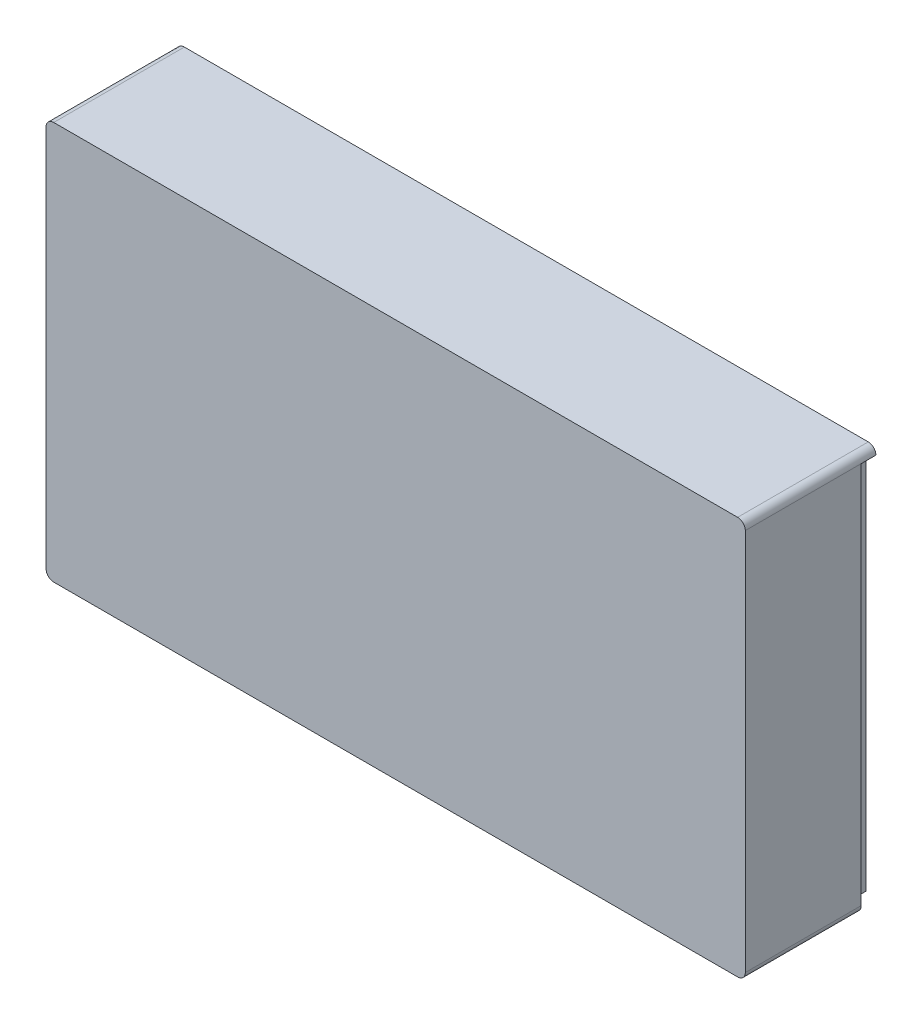
SolidWorks part; units mm, degrees
material "PETG"
ref_plane "Front Plane" through (0, 0, 0) normal (0, 0, 1) x (1, 0, 0)
ref_plane "Top Plane" through (0, 0, 0) normal (0, 1, 0) x (1, 0, 0)
ref_plane "Right Plane" through (0, 0, 0) normal (1, 0, 0) x (0, 0, -1)
sketch "Sketch2" plane through (0, 0, 0) normal (0, 0, 1) x (1, 0, 0)
  line L1 (-145, 82.55) -> (145, 82.55)
  line L2 (-145, 82.55) -> (-145, -82.55)
  line L3 (-145, -82.55) -> (145, -82.55)
  line L4 (145, 82.55) -> (145, -82.55)
  line L5 (133.825, 71.375) -> (133.825, -71.375)
  line L7 (-133.825, 71.375) -> (-133.825, -71.375)
  line L8 (-133.825, 71.375) -> (133.825, 71.375) construction
  line L9 (-133.825, 71.375) -> (-133.825, 79.375)
  line L10 (-133.825, 79.375) -> (133.825, 79.375)
  line L11 (133.825, 79.375) -> (133.825, 71.375)
  line L12 (133.825, -71.375) -> (133.825, -79.375)
  line L13 (-133.825, -71.375) -> (133.825, -71.375) construction
  line L14 (133.825, -79.375) -> (-133.825, -79.375)
  line L15 (-133.825, -79.375) -> (-133.825, -71.375)
  point P4 (0, 82.55)
  point P6 (145, 0)
  dimension "D1" = 290
  dimension "D2" = 165.1
  dimension "D4" = 3.175
  dimension "D5" = 3.175
  dimension "D3" = 11.175
extrude "Boss-Extrude1" add sketch "Sketch2" along normal blind 51
sketch "Sketch3" plane through (0, 0, 51) normal (0, 0, 1) x (1, 0, 0)
  line L0 (145, 82.55) -> (-145, 82.55) construction
  line L1 (-145, 82.55) -> (145, 82.55)
  line L2 (-145, 82.55) -> (-145, -82.55)
  line L3 (-145, -82.55) -> (145, -82.55)
  line L4 (145, 82.55) -> (145, -82.55)
extrude "Boss-Extrude2" add sketch "Sketch3" along normal blind 3.175
sketch "Sketch4" plane through (0, -82.55, 0) normal (0, -1, 0) x (1, 0, 0)
  line L0 (145, 54.175) -> (145, 0) construction
  line L1 (140.9, 2.9) -> (136.9, 2.9)
  line L2 (145, 2.9) -> (145, 6.1)
  line L3 (145, 6.1) -> (136.9, 6.1)
  line L4 (136.9, 2.9) -> (136.9, 6.1)
  line L5 (-145, 0) -> (145, 0) construction
  line L8 (140.9, 2.9) -> (140.9, 0)
  line L9 (140.9, 0) -> (145, 0)
  line L10 (145, 2.9) -> (145, 0)
  dimension "D1" = 2.9
  dimension "D2" = 3.2
  dimension "D3" = 8.1
  dimension "D4" = 4.1
extrude "Cut-Extrude1" cut sketch "Sketch4" against normal up to surface (161.925 mm away) up to face at (0, 79.375, 25.5)
mirror "Mirror1" about plane through (0, 0, 0) normal (1, 0, 0) of "Cut-Extrude1"
ref_plane "Plane2" through (0, 79.375, 0) normal (0, 1, 0) x (1, 0, 0)
sketch "Sketch7" plane through (0, 79.375, 0) normal (0, 1, 0) x (1, 0, 0)
  line L0 (133.825, -51) -> (133.825, 0) construction
  line L1 (133.825, -51) -> (133.825, 0)
  line L2 (136.9, -6.1) -> (145, -6.1) construction
  line L3 (133.825, -9.275) -> (141, -9.275)
  line L4 (133.825, -9.275) -> (133.825, -51)
  line L5 (133.825, -51) -> (141, -51)
  line L6 (141, -9.275) -> (141, -51)
  line L7 (136.9, -6.1) -> (145, -6.1)
  line L8 (145, -54.175) -> (145, 0) construction
  dimension "D1" = 3.175
  dimension "D2" = 4
extrude "Cut-Extrude3" cut sketch "Sketch7" against normal up to surface (158.75 mm away) contours L6 L3 L1 L5 up to face at (0, -79.375, 25.5)
mirror "Mirror4" about plane through (0, 0, 0) normal (1, 0, 0) of "Cut-Extrude3"
fillet "Fillet1" radius 3.175 4 edges at (145, -82.55, 30.1375) (-145, -82.55, 30.1375) (-145, 82.55, 27.0875) (145, 82.55, 27.0875)
sketch "Sketch8" plane through (0, -82.55, 0) normal (0, -1, 0) x (1, 0, 0)
  line L0 (-145, 6.1) -> (-145, 54.175) construction
  line L1 (145, 0) -> (-145, 0)
  line L2 (145, 0) -> (145, 6.1)
  line L3 (145, 6.1) -> (-145, 6.1)
  line L4 (-145, 0) -> (-145, 6.1)
  line L5 (-141.825, 6.1) -> (-136.9, 6.1) construction
extrude "Cut-Extrude4" cut sketch "Sketch8" against normal blind 3.25
